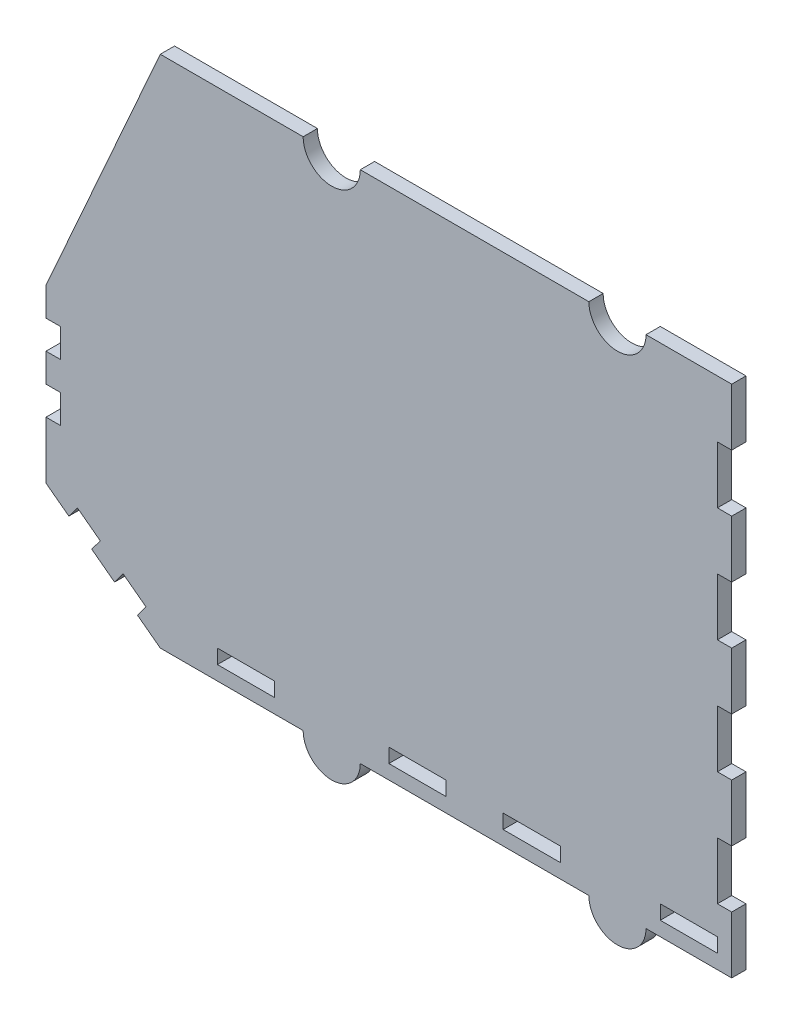
SolidWorks part; units mm, degrees
ref_plane "Front Plane" through (0, 0, 0) normal (0, 0, 1) x (1, 0, 0)
ref_plane "Top Plane" through (0, 0, 0) normal (0, 1, 0) x (1, 0, 0)
ref_plane "Right Plane" through (0, 0, 0) normal (1, 0, 0) x (0, 0, -1)
sketch "Sketch1" plane through (0, 0, 0) normal (0, 0, 1) x (1, 0, 0)
  line L0 (20, 0) -> (45, 0)
  line L1 (120, 0) -> (120, 10)
  line L2 (120, 90) -> (105, 90)
  line L3 (20, 90) -> (0, 45)
  line L4 (0, 45) -> (0, 40)
  line L5 (0, 15) -> (4, 12)
  line L6 (0, 25) -> (0, 15)
  line L7 (4, 12) -> (5.5, 14)
  line L8 (8, 9) -> (9.5, 11)
  line L9 (5.5, 14) -> (9.5, 11)
  line L10 (8, 9) -> (12, 6)
  line L11 (12, 6) -> (13.5, 8)
  line L12 (16, 3) -> (17.5, 5)
  line L13 (13.5, 8) -> (17.5, 5)
  line L14 (120, 80) -> (120, 90)
  line L15 (0, 40) -> (2.5, 40)
  line L16 (0, 35) -> (2.5, 35)
  line L17 (2.5, 40) -> (2.5, 35)
  line L18 (120, 80) -> (117.5, 80)
  line L19 (0, 30) -> (2.5, 30)
  line L20 (0, 25) -> (2.5, 25)
  line L21 (2.5, 30) -> (2.5, 25)
  line L22 (16, 3) -> (20, 0)
  line L23 (0, 35) -> (0, 30)
  line L24 (120, 70) -> (117.5, 70)
  line L25 (117.5, 80) -> (117.5, 70)
  line L26 (120, 60) -> (120, 70)
  line L27 (120, 60) -> (117.5, 60)
  line L28 (120, 50) -> (117.5, 50)
  line L29 (117.5, 60) -> (117.5, 50)
  line L30 (120, 40) -> (120, 50)
  line L31 (120, 40) -> (117.5, 40)
  line L32 (120, 30) -> (117.5, 30)
  line L33 (117.5, 40) -> (117.5, 30)
  line L34 (0, 15) -> (20, 0) construction
  line L35 (120, 20) -> (117.5, 20)
  line L36 (120, 10) -> (117.5, 10)
  line L37 (117.5, 20) -> (117.5, 10)
  line L38 (120, 20) -> (120, 30)
  line L39 (45, 90) -> (20, 90)
  line L40 (95, 90) -> (55, 90)
  line L42 (0, 15) -> (1.5, 17) construction
  line L43 (20, 0) -> (21.5, 2) construction
  line L44 (1.5, 17) -> (21.5, 2) construction
  line L45 (0, 15) -> (0, 45) construction
  line L46 (0, 15) -> (2.5, 15) construction
  line L47 (0, 45) -> (2.5, 45) construction
  line L48 (2.5, 15) -> (2.5, 45) construction
  line L49 (105, 0) -> (120, 0)
  line L50 (117.5, 5) -> (107.5, 5)
  line L51 (55, 0) -> (95, 0)
  line L52 (117.5, 5) -> (117.5, 2.5)
  line L53 (117.5, 2.5) -> (107.5, 2.5)
  line L54 (107.5, 5) -> (107.5, 2.5)
  line L55 (90, 5) -> (80, 5)
  line L56 (90, 5) -> (90, 2.5)
  line L57 (90, 2.5) -> (80, 2.5)
  line L58 (80, 5) -> (80, 2.5)
  line L59 (70, 5) -> (60, 5)
  line L60 (70, 5) -> (70, 2.5)
  line L61 (70, 2.5) -> (60, 2.5)
  line L62 (60, 5) -> (60, 2.5)
  line L63 (40, 5) -> (30, 5)
  line L64 (40, 5) -> (40, 2.5)
  line L65 (40, 2.5) -> (30, 2.5)
  line L66 (30, 5) -> (30, 2.5)
  arc A0 (95, 0) -> (105, 0) centre (100, 0) ccw
  arc A1 (45, 0) -> (55, 0) centre (50, 0) ccw
  arc A2 (45, 90) -> (55, 90) centre (50, 90) ccw
  arc A3 (95, 90) -> (105, 90) centre (100, 90) ccw
  dimension "D7" = 10
  dimension "D21" = 10
  dimension "D1" = 120
  dimension "D2" = 100
  dimension "D3" = 90
  dimension "D4" = 45
  dimension "D5" = 30
  dimension "D6" = 2.5
  dimension "t" = 2.5
  dimension "D8" = 5
  dimension "D9" = 5
  dimension "D10" = 5
  dimension "D11" = 5
  dimension "D12" = 2.5
  dimension "D13" = 5
  dimension "D14" = 10
  dimension "D15" = 5
  dimension "D16" = 2.5
  dimension "D17" = 10
  dimension "D18" = 10
  dimension "D20" = 10
  dimension "D22" = 20
  dimension "D23" = 50
  dimension "D24" = 100
  dimension "D25" = 2.5
  dimension "D26" = 2.5
  dimension "D27" = 10
  dimension "D28" = 2.5
  dimension "D29" = 5
  dimension "D30" = 10
  dimension "D31" = 5
  dimension "D19" = 4
extrude "Boss-Extrude1" add sketch "Sketch1" along normal blind 2.5
equation "\"t\"= 2.5"
equation "\"t@Sketch1\"=\"t\""
equation "\"D6@Sketch1\"=\"t\""
equation "\"D12@Sketch1\"=\"t\""
equation "\"D16@Sketch1\"=\"t\""
equation "\"height\"=90"
equation "\"D3@Sketch1\"=\"height\""
equation "\"bottom_depth\"= 100"
equation "\"D2@Sketch1\"=\"bottom_depth\""
equation "\"total_depth\"=120"
equation "\"D1@Sketch1\"=\"total_depth\""
equation "\"D24@Sketch1\"=\"bottom_depth\""
equation "\"D1@Boss-Extrude1\"=\"t\""
equation "\"D25@Sketch1\"=\"t\""
equation "\"D26@Sketch1\"=\"t\""
